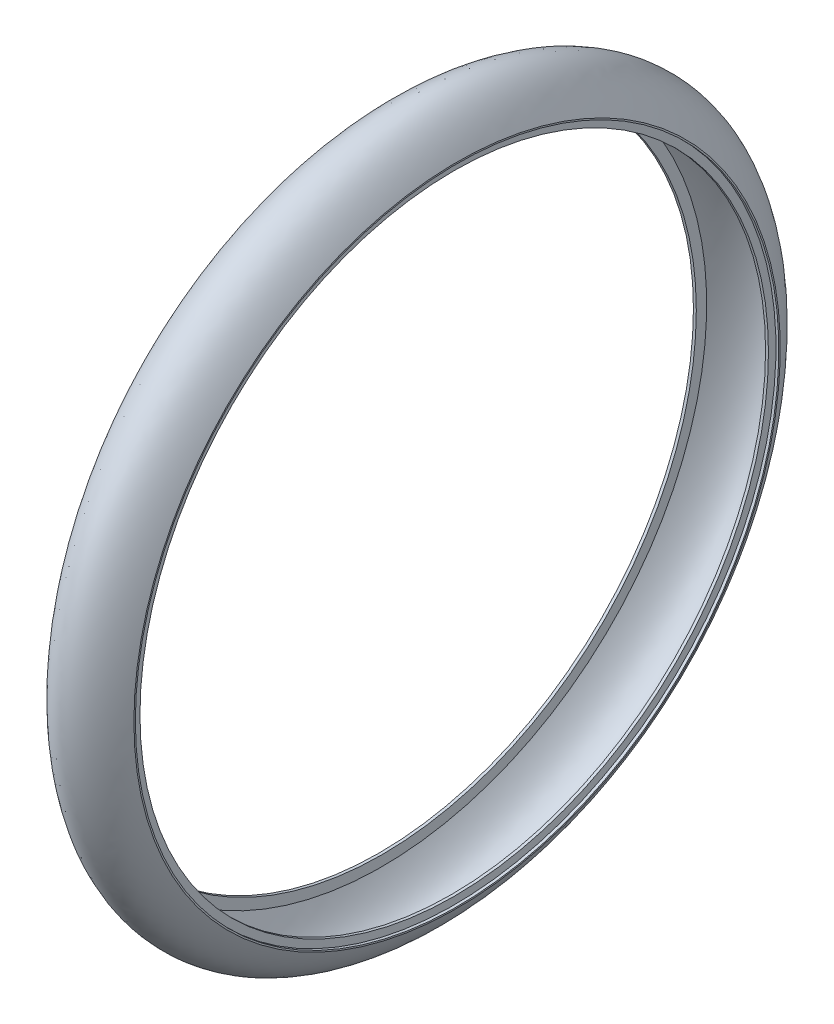
SolidWorks part; units mm, degrees
ref_plane "Front Plane" through (0, 0, 0) normal (0, 0, 1) x (1, 0, 0)
ref_plane "Top Plane" through (0, 0, 0) normal (0, 1, 0) x (1, 0, 0)
ref_plane "Right Plane" through (0, 0, 0) normal (1, 0, 0) x (0, 0, -1)
sketch "Sketch2" plane through (0, 0, 0) normal (0, 0, 1) x (1, 0, 0)
  line L0 (-92.7299, 0) -> (87.1938, 0) construction
  line L1 (0, 0) -> (0, 279.3868) construction
  line L2 (28, 223) -> (28, 224)
  line L3 (-26, 217.8) -> (-26, 223)
  line L4 (-26, 223) -> (-28, 223)
  line L5 (-28, 223) -> (-28, 224)
  line L6 (26, 223) -> (28, 223)
  line L7 (26, 217.8) -> (26, 223)
  line L8 (-24, 217.8) -> (-24, 225)
  line L9 (-24, 225) -> (-25.0812, 225)
  line L10 (-25.0812, 225) -> (-25.0812, 225)
  line L11 (25.1334, 225) -> (25.1334, 225)
  line L12 (24, 225) -> (25.1334, 225)
  line L13 (24, 217.8) -> (24, 225)
  line L14 (-24, 217.8) -> (-26, 217.8)
  line L15 (26, 217.8) -> (24, 217.8)
  spline S0 degree 2 poles (-28, 224) (0.6371, 273.2823) (28, 224) knots 0 0 0 1 1 1
  spline S1 degree 1 poles (-25.0812, 225) (25.1334, 225) knots 0 0 1 1 construction
  spline S2 degree 3 poles (-25.0812, 225) (-24.8038, 225.4578) (-24.2376, 226.3776) (-23.1198, 228.1369) (-21.7225, 230.2302) (-20.0553, 232.5584) (-17.8433, 235.4223) (-15.1033, 238.5491) (-11.8666, 241.5775) (-8.6976, 243.8885) (-4.579, 246.0345) (0.335, 247.0474) (5.2103, 246.0291) (9.2611, 243.8847) (12.3626, 241.5756) (15.5151, 238.5489) (18.1708, 235.4229) (20.3065, 232.5592) (21.9121, 230.2309) (23.2543, 228.1374) (24.3259, 226.3779) (24.868, 225.4578) (25.1334, 225) knots 0.021109 0.021109 0.021109 0.021109 0.03608 0.051051 0.080993 0.110934 0.140876 0.20076 0.260643 0.320527 0.38041 0.500177 0.619944 0.679828 0.739711 0.799595 0.859478 0.88942 0.919362 0.949304 0.964274 0.979245 0.979245 0.979245 0.979245
  point P5 (0, 217.8)
  point P23 (0, 248.3096)
  dimension "D1" = 217.8
  dimension "D2" = 2
  dimension "D3" = 5.2
  dimension "D4" = 2
  dimension "D5" = 1
  dimension "D6" = 217.8
  dimension "D7" = 48
revolve "Revolve2" add sketch "Sketch2" angle 360 about L0
